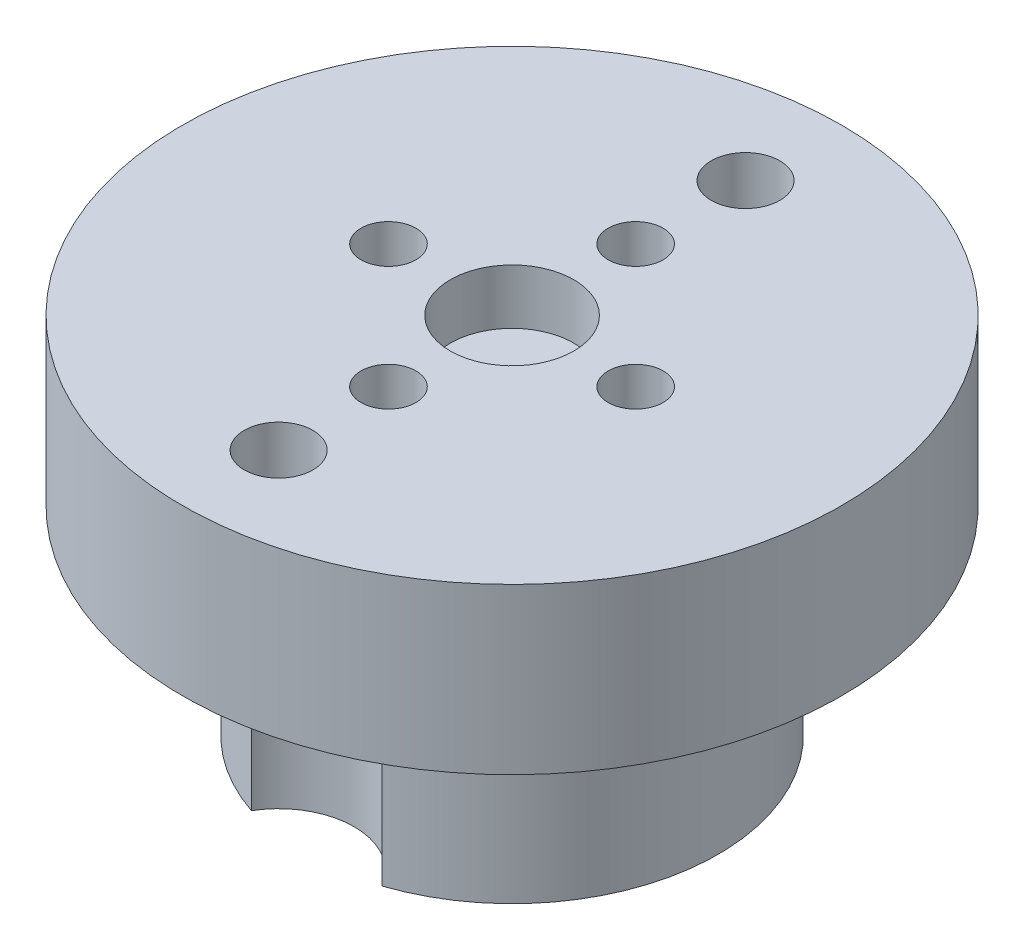
SolidWorks part; units mm, degrees
material "ABS PC"
ref_plane "Front Plane" through (0, 0, 0) normal (0, 0, 1) x (1, 0, 0)
ref_plane "Top Plane" through (0, 0, 0) normal (0, 1, 0) x (1, 0, 0)
ref_plane "Right Plane" through (0, 0, 0) normal (1, 0, 0) x (0, 0, -1)
sketch "Sketch1" plane through (0, 0, 0) normal (0, 0, 1) x (1, 0, 0)
  line L0 (0, 0) -> (0, 15.6368) construction
  line L1 (0, 13.25) -> (0, 0)
  line L2 (0, 13.25) -> (12, 13.25)
  line L3 (8.5, 5.25) -> (8.5, 7.25)
  line L4 (8.5, 5.25) -> (7.5, 5.25)
  line L5 (7.5, 5.25) -> (7.5, 0)
  line L7 (8.5, 7.25) -> (12, 7.25)
  line L8 (12, 7.25) -> (12, 13.25)
  line L10 (0, 0) -> (7.5, 0)
  dimension "D1" = 7.5
  dimension "D2" = 1
  dimension "D3" = 5.25
  dimension "D4" = 2
  dimension "D5" = 12
  dimension "D6" = 6
revolve "Revolve1" add sketch "Sketch1" angle 360 about L0
sketch "Sketch2" plane through (0, 13.25, 0) normal (0, 1, 0) x (1, 0, 0)
  circle A1 centre (4.5, 0) radius 1
  dimension "D3" = 2
  dimension "D4" = 4.5
extrude "Cut-Extrude1" cut sketch "Sketch2" against normal through all
pattern_circular "CirPattern1" count 4 over 360 about axis through (0, 0, 0) along (0, 1, 0) of "Cut-Extrude1"
sketch "Sketch5" plane through (0, 13.25, 0) normal (0, 1, 0) x (1, 0, 0)
  circle A0 centre (0, 8.5) radius 1.25
  circle A1 centre (0, -8.5) radius 1.25
  dimension "D1" = 2.5
  dimension "D2" = 8.5
  dimension "D3" = 8.5
extrude "Cut-Extrude4" cut sketch "Sketch5" against normal blind 10
sketch "Sketch3" plane through (0, 0, 0) normal (0, -1, 0) x (1, 0, 0)
  circle A0 centre (0, 8.5) radius 2.75
  circle A1 centre (0, 8.5) radius 1.25 construction
  circle A2 centre (0, -8.5) radius 2.75
  circle A4 centre (8.5, 0) radius 2.75 [skipped]
  circle A5 centre (-8.5, 0) radius 2.75 [skipped]
  point P12 (0, 0)
  dimension "D1" = 5.5
  dimension "D2" = 4
extrude "Cut-Extrude2" cut sketch "Sketch3" against normal blind 8
sketch "Sketch4" plane through (0, 13.25, 0) normal (0, 1, 0) x (1, 0, 0)
  circle A0 centre (0, 0) radius 2.25
  dimension "D1" = 4.5
extrude "Cut-Extrude3" cut sketch "Sketch4" against normal blind 2
